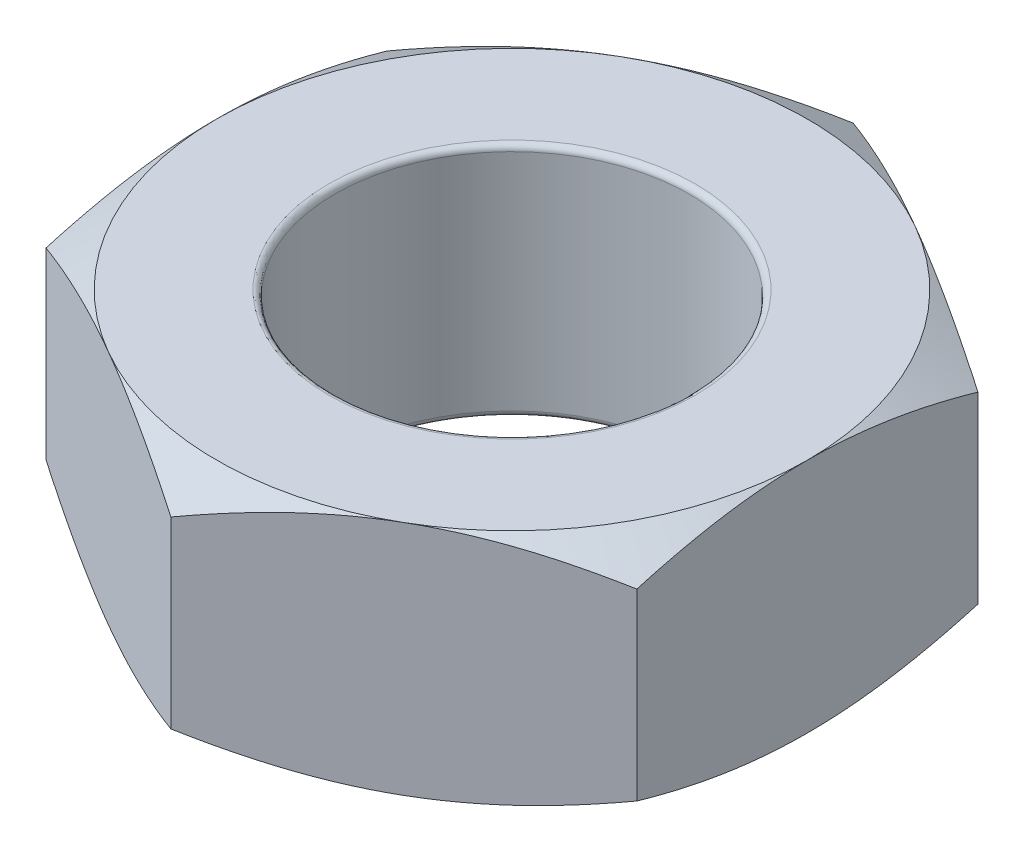
SolidWorks part; units mm, degrees
ref_plane "Front Plane" through (0, 0, 0) normal (0, 0, 1) x (1, 0, 0)
ref_plane "Top Plane" through (0, 0, 0) normal (0, 1, 0) x (1, 0, 0)
ref_plane "Right Plane" through (0, 0, 0) normal (1, 0, 0) x (0, 0, -1)
sketch "Sketch1" plane through (0, 0, 0) normal (0, 1, 0) x (1, 0, 0)
  line L1 (0, 2.8868) -> (-2.5, 1.4434)
  line L2 (-2.5, 1.4434) -> (-2.5, -1.4434)
  line L3 (-2.5, -1.4434) -> (0, -2.8868)
  line L4 (0, -2.8868) -> (2.5, -1.4434)
  line L5 (2.5, -1.4434) -> (2.5, 1.4434)
  line L6 (2.5, 1.4434) -> (0, 2.8868)
  circle A0 centre (0, 0) radius 1.5
  circle A1 centre (0, 0) radius 2.5 construction
  dimension "D1" = 3
  dimension "D2" = 5
extrude "Boss-Extrude1" add sketch "Sketch1" along normal blind 2
sketch "Sketch2" plane through (0, 2, 0) normal (0, 1, 0) x (1, 0, 0)
  circle A0 centre (0, 0) radius 2.5 construction
  circle A1 centre (0, 0) radius 2.5
extrude "Cut-Extrude1" cut sketch "Sketch2" against normal blind 2 draft 60 flip side to cut
sketch "Sketch3" plane through (0, 0, 0) normal (0, -1, 0) x (1, 0, 0)
  circle A0 centre (0, 0) radius 2.5 construction
  circle A1 centre (0, 0) radius 2.5
extrude "Cut-Extrude2" cut sketch "Sketch3" against normal blind 2 draft 60 flip side to cut
fillet "Fillet1" radius 0.05 2 edges at (0, 0, 1.5) (0, 2, 1.5)
